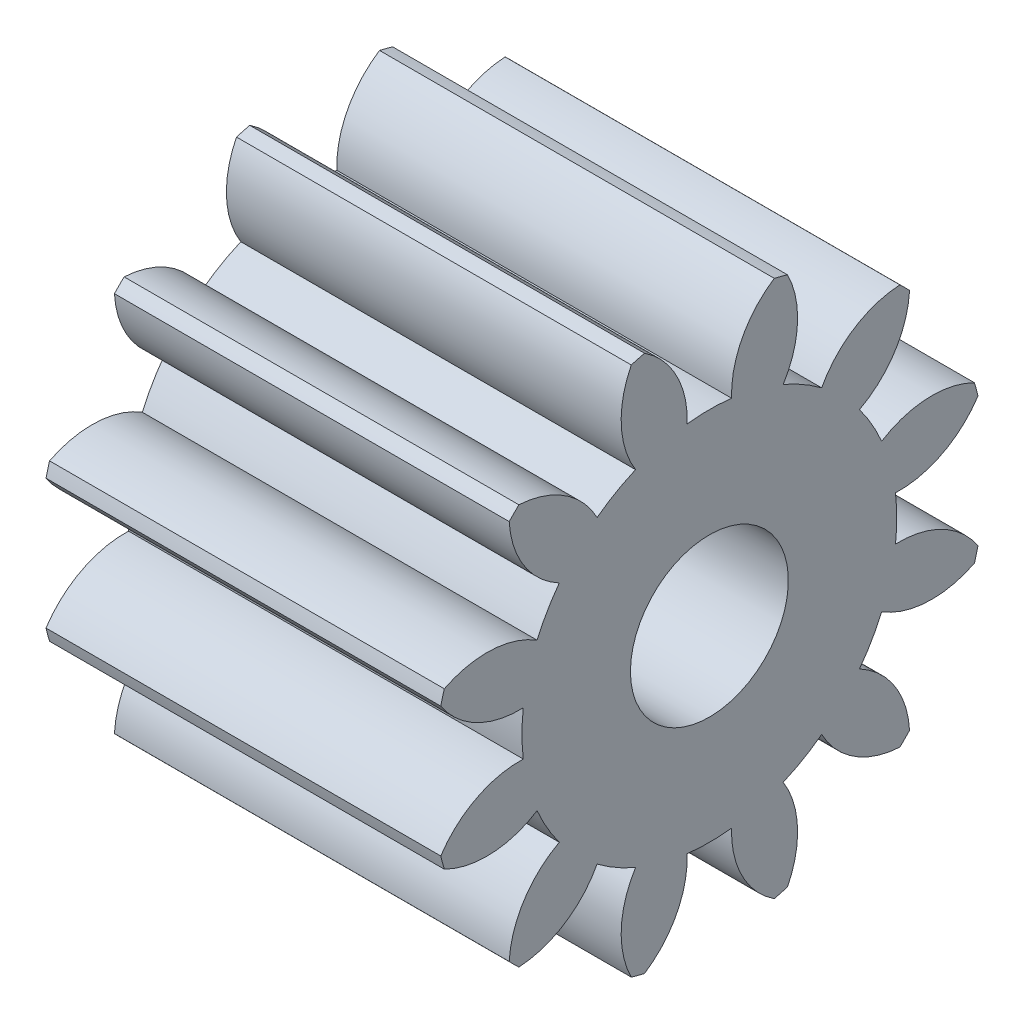
SolidWorks part; units mm, degrees
ref_plane "Plane1" through (0, 0, 0) normal (0, 0, 1) x (1, 0, 0)
ref_plane "Plane2" through (0, 0, 0) normal (0, 1, 0) x (1, 0, 0)
ref_plane "Plane3" through (0, 0, 0) normal (1, 0, 0) x (0, 0, -1)
sketch "HoldingSke" plane through (0, 0, 0) normal (0, 1, 0) x (1, 0, 0)
  line L0 (0, 0) -> (1.9563, -0.4158)
  line L1 (-15, 0) -> (100, 0) construction
  line L2 (0, 0) -> (-2.1039, 2.3779)
  line L3 (0, 0) -> (-11.863, 4.5341)
  line L4 (0, 0) -> (8.4473, 1.7955)
  line L5 (0, 0) -> (-46.8476, -17.4728)
  line L6 (0, 0) -> (-4.1448, -2.7965)
  line L7 (-2.1039, 2.3779) -> (8.6586, 51.2059)
  line L8 (-76.2, 54.61) -> (-75.9, 54.61)
  line L9 (-71.009, 38.7566) -> (-53.1078, 45.2721)
  line L10 (-76.2, 71.12) -> (104.1128, 71.12)
  line L11 (0, 0) -> (-5, 0)
  line L12 (-76.2, 101.6) -> (-76.181, 101.6)
  line L13 (24.9733, 27.94) -> (52.9518, 28.4284)
  line L14 (24.9733, 27.94) -> (24.9743, 27.94)
  line L15 (24.9733, 27.94) -> (100.4006, 29.5858)
  line L16 (-63.627, -0.5) -> (-12.827, -0.5)
  circle A0 centre (0, 0) radius 1
  circle A1 centre (0, 0) radius 2.374
  circle A2 centre (0, 0) radius 37.5
  circle A3 centre (0, 0) radius 1
  dimension "MHD" = 4.748
  dimension "Hub_dia" = 75
  dimension "Bore" = 2
  dimension "MBD" = 2
  dimension "Num_teeth" = 12
  dimension "Pitch" = 2
  dimension "Overall_len" = 50
  dimension "Show_teeth" = 12
  dimension "Thickness" = 5
  dimension "OAL" = 50.0001
  dimension "T_dim" = 0.3
  dimension "Ap" = 20
  dimension "H" = 19.05
  dimension "Pitch_radius" = 180.3128
  dimension "Width" = 5
  dimension "Backlash" = 0.019
  dimension "Addendum_fac" = 1
  dimension "Dedendum_fac" = 1.25
  dimension "Clearance_fac" = 0.25
  dimension "Dedendum_add" = 0.001
  dimension "Module" = 0.5
sketch "BasProSke" plane through (0, 0, 0) normal (0, 1, 0) x (1, 0, 0)
  line L0 (-10, 0) -> (60, 0) construction
  line L1 (0, 0) -> (0, 3.5)
  line L2 (0, 0) -> (5, 0)
  line L3 (5, 0) -> (5, 3.5)
  line L4 (5, 3.5) -> (0, 3.5)
  dimension "Thickness" = 5
  dimension "Diameter" = 7
revolve "Base-Revolve" add sketch "BasProSke" angle 360 about L0
sketch "TooCutSke" plane through (0, 0, 0) normal (1, 0, 0) x (0, 0, -1)
  line L1 (0, 0) -> (0, 107) construction
  line L2 (0, 0) -> (-0.4248, 2.9698) construction
  line L3 (0, 0) -> (-1.5418, 5.7541) construction
  line L4 (-0.4248, 2.9698) -> (-0.7709, 2.877) construction
  arc A0 (0.2811, 2.3573) -> (-0.2811, 2.3573) centre (0, 0) ccw
  arc A1 (0.8514, 3.421) -> (-0.8514, 3.421) centre (0, 0) ccw
  circle A2 centre (0, 0) radius 3 construction
  circle A3 centre (0, 0) radius 2.8191 construction
  arc A4 (-0.2811, 2.3573) -> (-0.8514, 3.421) centre (-1.4804, 2.3991) ccw
  arc A5 (0.8514, 3.421) -> (0.2811, 2.3573) centre (1.4804, 2.3991) ccw
  dimension "Root_dia" = 4.748
  dimension "Overcut_dia" = 7.0508
  dimension "Pitch_dia" = 6
  dimension "Base_dia" = 5.6382
  dimension "Flank_rad" = 1.2
  dimension "Half_ang" = 15
  dimension "Half_CT" = 0.3583
extrude "ToothCut" cut sketch "TooCutSke" along normal through all
fillet "Breaks" [suppressed] radius 0.01
fillet "RootFillets" [suppressed] radius 0.126
pattern_circular "TeethCuts" count 12 every 30 about axis through (-10, 0, 0) along (1, 0, 0) of "ToothCut", "RootFillets", "Breaks"
sketch "HubNeaOneSke" plane through (0, 0, 0) normal (-1, 0, 0) x (0, 0, 1)
  circle A0 centre (0, 0) radius 2.374
  dimension "Diameter" = 4.748
extrude "HubNearOne" [suppressed] add sketch "HubNeaOneSke" along normal blind 45.0001
sketch "HubNeaBotSke" plane through (0, 0, 0) normal (-1, 0, 0) x (0, 0, 1)
  circle A0 centre (0, 0) radius 2.374
  dimension "Diameter" = 4.748
extrude "HubNearBoth" [suppressed] add sketch "HubNeaBotSke" along normal blind 22.5
ref_plane "FarPln" through (5, 0, 0) normal (1, 0, 0) x (0, 0, -1)
sketch "HubFarSke" plane through (5, 0, 0) normal (1, 0, 0) x (0, 0, -1)
  circle A0 centre (0, 0) radius 2.374
  dimension "Diameter" = 4.748
extrude "HubFar" [suppressed] add sketch "HubFarSke" along normal blind 22.5
sketch "BorSke" plane through (0, 0, 0) normal (1, 0, 0) x (0, 0, -1)
  circle A0 centre (0, 0) radius 1
  dimension "Diameter" = 2
extrude "Bore" cut sketch "BorSke" along normal mid plane 100.0001
sketch "KeySke" plane through (0, 0, 0) normal (1, 0, 0) x (0, 0, -1)
  line L0 (-0.4, 0) -> (-0.4, 1.3)
  line L1 (-0.4, 1.3) -> (0.4, 1.3)
  line L2 (0.4, 1.3) -> (0.4, 0)
  line L3 (0, 0) -> (0, 34) construction
  line L4 (-0.4, 0) -> (0.4, 0)
  dimension "Offset" = 1.3
  dimension "Width" = 0.8
extrude "Keyway" [suppressed] cut sketch "KeySke" along normal mid plane 100.0001
pattern_circular "Keyway2" [suppressed] count 2 every 90 about axis through (-10, 0, 0) along (1, 0, 0)
equation "' \"Module@HoldingSke\" = 6.35"
equation "' \"Num_teeth@HoldingSke\" = 12"
equation "' \"Ap@HoldingSke\" =  20"
equation "' \"Ap@HoldingSke\" = 20"
equation "' \"Width@HoldingSke\" = 0.5 * 25.4"
equation "' \"Hub_dia@HoldingSke\"= 1 * 25.4"
equation "' \"Hub_dia@HoldingSke\" = 1 * 25.4"
equation "' \"Overall_len@HoldingSke\" = 1.0 * 25.4"
equation "' \"Bore@HoldingSke\" = 0.75 * 25.4"
equation "' \"T_dim@HoldingSke\" = 0.1 * 25.4"
equation "' \"Width@KeySke\" = 0.25 * 25.4"
equation "' \"Show_teeth@HoldingSke\" = 13"
equation "' \"Backlash@HoldingSke\" = 0.009 * 25.4"
equation "' \"Addendum_fac@HoldingSke\" = 1.0"
equation "' \"Dedendum_fac@HoldingSke\" = 1.25"
equation "' \"Dedendum_add@HoldingSke\" = 0.00005 * 25.4"
equation "' \"Clearance_fac@HoldingSke\" = 0.25"
equation "\"Pitch@HoldingSke\" = 1 / \"Module@HoldingSke\""
equation "\"Overcut_dia@TooCutSke\" = (\"Num_teeth@HoldingSke\" + 2 * \"Addendum_fac@HoldingSke\") / \"Pitch@HoldingSke\" + 0.002 * 25.4"
equation "\"Pitch_dia@TooCutSke\" = \"Num_teeth@HoldingSke\" / \"Pitch@HoldingSke\""
equation "\"Base_dia@TooCutSke\" = \"Num_teeth@HoldingSke\" / \"Pitch@HoldingSke\" * cos((\"Ap@HoldingSke\"  * 3.14159265 / 180))"
equation "\"Root_dia@TooCutSke\" = (\"Num_teeth@HoldingSke\" + 2) / \"Pitch@HoldingSke\" - 2 * (\"Addendum_fac@HoldingSke\" + \"Dedendum_fac@HoldingSke\") / \"Pitch@HoldingSke\" - \"Dedendum_add@HoldingSke\" * 2"
equation "\"Half_ang@TooCutSke\" = 180 / \"Num_teeth@HoldingSke\""
equation "\"Half_CT@TooCutSke\" = \"Num_teeth@HoldingSke\" / \"Pitch@HoldingSke\" * sin((3.14159265 / 2 / \"Num_teeth@HoldingSke\")) / 2 - 7 * \"Backlash@HoldingSke\" / 4"
equation "\"Flank_rad@TooCutSke\" = \"Num_teeth@HoldingSke\" / \"Pitch@HoldingSke\" / 5"
equation "\"Radius@RootFillets\" = \"Clearance_fac@HoldingSke\" / \"Pitch@HoldingSke\" + \"Dedendum_add@HoldingSke\""
equation "\"Break_rad@Breaks\" = 0.02 / \"Pitch@HoldingSke\""
equation "\"Thickness@HoldingSke\" = \"Width@HoldingSke\""
equation "\"OAL@HoldingSke\" = \"Thickness@HoldingSke\""
equation "\"MHD@HoldingSke\" = (\"Num_teeth@HoldingSke\" + 2) / \"Pitch@HoldingSke\" - 2 * (\"Addendum_fac@HoldingSke\" + \"Dedendum_fac@HoldingSke\")  / \"Pitch@HoldingSke\" - \"Dedendum_add@HoldingSke\" * 2"
equation "\"MBD@HoldingSke\" = (\"Num_teeth@HoldingSke\" + 2) / \"Pitch@HoldingSke\" - 2 * (\"Addendum_fac@HoldingSke\" + \"Dedendum_fac@HoldingSke\")  / \"Pitch@HoldingSke\" - \"Dedendum_add@HoldingSke\" * 2 - 0.002 * 25.4"
equation "\"MHD@HoldingSke\" = ((sgn( \"MHD@HoldingSke\" - \"Hub_dia@HoldingSke\" )-1)*( \"MHD@HoldingSke\" - \"Hub_dia@HoldingSke\" ))/-2+ \"Hub_dia@HoldingSke\""
equation "\"MBD@HoldingSke\" = ((sgn( \"MBD@HoldingSke\" - \"Bore@HoldingSke\" )-1)*( \"MBD@HoldingSke\" - \"Bore@HoldingSke\" ))/-2+ \"Bore@HoldingSke\""
equation "\"OAL@HoldingSke\" = ((sgn( \"OAL@HoldingSke\" - \"Overall_len@HoldingSke\" )+1)*( \"OAL@HoldingSke\" - \"Overall_len@HoldingSke\" ))/2 + \"Overall_len@HoldingSke\" + 0.000002 * 25.4"
equation "\"Num_teeth@TeethCuts\" = int( \"Show_teeth@HoldingSke\" ) + 1"
equation "\"Num_teeth@TeethCuts\" = ((sgn( \"Num_teeth@TeethCuts\" - \"Num_teeth@HoldingSke\" )-1)*( \"Num_teeth@TeethCuts\" - \"Num_teeth@HoldingSke\" ))/-2+ \"Num_teeth@HoldingSke\""
equation "\"Num_teeth@TeethCuts\" = ((sgn( \"Num_teeth@TeethCuts\" - 2.0)+1)*( \"Num_teeth@TeethCuts\" - 2.0))/2 +2.0"
equation "\"Angle@TeethCuts\" = 360.0 / \"Num_teeth@HoldingSke\""
equation "\"Diameter@BasProSke\" = (\"Num_teeth@HoldingSke\" + 2 * \"Addendum_fac@HoldingSke\") / \"Pitch@HoldingSke\""
equation "\"Thickness@BasProSke\"  = \"Thickness@HoldingSke\""
equation "' \"Fillet_rad@BasProSke\" =  \"Thickness@HoldingSke\" * 0.05"
equation "' \"Fillet_rad@BasProSke\" = \"Thickness@HoldingSke\" * 0.05"
equation "\"MHD@HoldingSke\" = ((sgn( \"MHD@HoldingSke\" - \"Root_dia@TooCutSke\" )-1)*( \"MHD@HoldingSke\" - \"Root_dia@TooCutSke\" ))/-2+ \"Root_dia@TooCutSke\""
equation "\"Diameter@HubNeaOneSke\" = \"MHD@HoldingSke\""
equation "\"Length@HubNearOne\" = \"OAL@HoldingSke\" - \"Thickness@BasProSke\""
equation "\"Diameter@HubNeaBotSke\" = \"MHD@HoldingSke\""
equation "\"Length@HubNearBoth\" = ( \"OAL@HoldingSke\" - \"Thickness@BasProSke\" ) / 2.0"
equation "\"Thickness@FarPln\" = \"Thickness@BasProSke\""
equation "\"Diameter@HubFarSke\" = \"MHD@HoldingSke\""
equation "\"Length@HubFar\" = ( \"OAL@HoldingSke\" - \"Thickness@BasProSke\" ) / 2.0"
equation "\"Diameter@BorSke\" = \"MBD@HoldingSke\""
equation "\"D1@Bore\" = \"OAL@HoldingSke\" * 2.0"
equation "\"D1@Keyway\" = \"OAL@HoldingSke\" * 2.0"
equation "\"Offset@KeySke\" = \"T_dim@HoldingSke\" + \"MBD@HoldingSke\" / 2.0"
